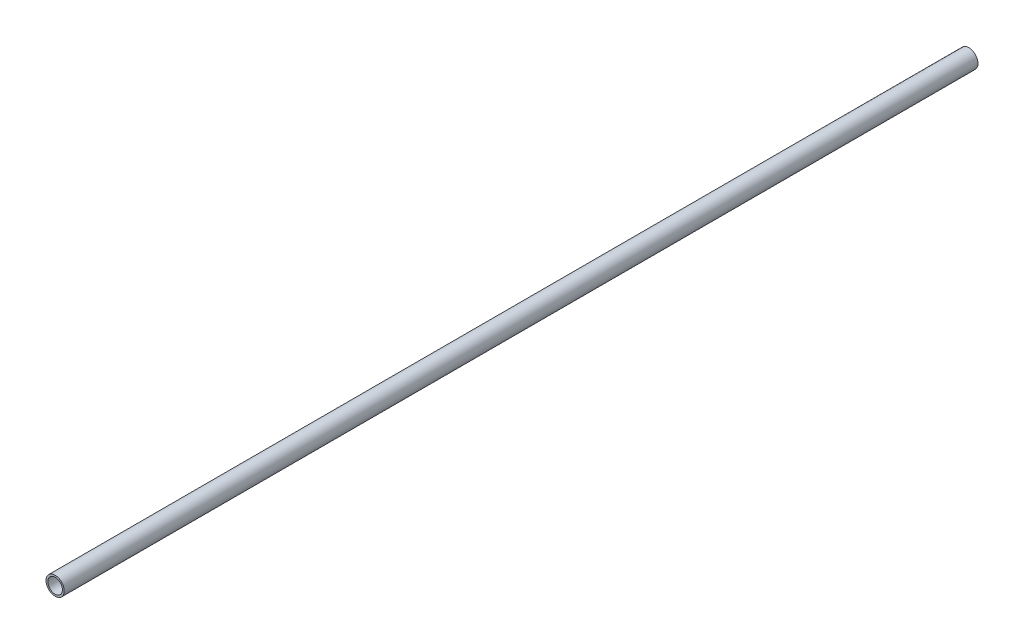
SolidWorks part; units mm, degrees
ref_plane "Piano frontale" through (0, 0, 0) normal (0, 0, 1) x (1, 0, 0)
ref_plane "Piano superiore" through (0, 0, 0) normal (0, 1, 0) x (1, 0, 0)
ref_plane "Piano destro" through (0, 0, 0) normal (1, 0, 0) x (0, 0, -1)
sketch "Schizzo1" plane through (0, 0, 0) normal (0, 0, 1) x (1, 0, 0)
  circle A0 centre (0, 0) radius 10
  circle A1 centre (0, 0) radius 8
  dimension "D1" = 20
  dimension "D2" = 2
extrude "Estrusione-Estrusione1" add sketch "Schizzo1" along normal blind 1000
